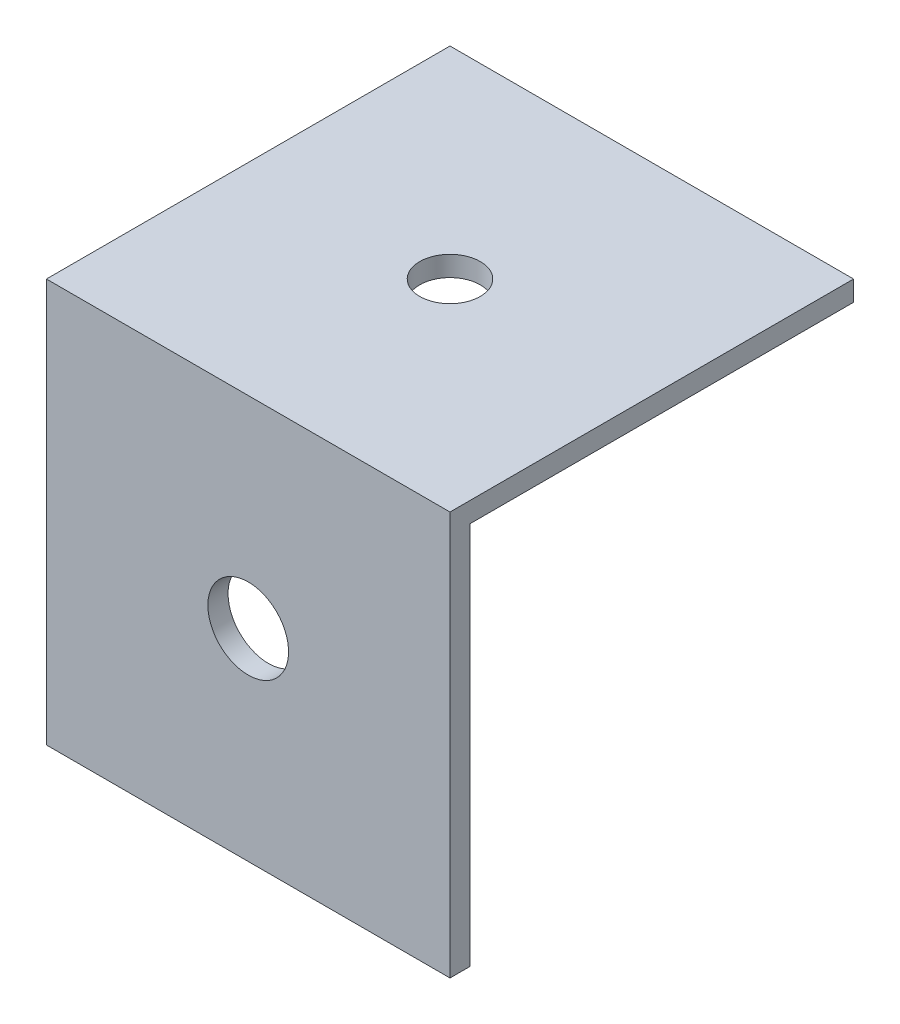
SolidWorks part; units mm, degrees
ref_plane "Front" through (0, 0, 0) normal (0, 0, 1) x (1, 0, 0)
ref_plane "Top" through (0, 0, 0) normal (0, 1, 0) x (1, 0, 0)
ref_plane "Right" through (0, 0, 0) normal (1, 0, 0) x (0, 0, -1)
sketch "草图1" plane through (0, 0, 0) normal (1, 0, 0) x (0, 0, -1)
  line L0 (0, 0) -> (0, 20)
  line L1 (0, 20) -> (20, 20)
  line L2 (20, 20) -> (20, 19)
  line L3 (20, 19) -> (1, 19)
  line L4 (1, 19) -> (1, 0)
  line L5 (1, 0) -> (0, 0)
  dimension "D1" = 20
  dimension "D2" = 20
  dimension "D3" = 1
  dimension "D4" = 19
extrude "凸台-拉伸1" add sketch "草图1" along normal blind 20
sketch "草图2" plane through (0, 0, -1) normal (0, 0, -1) x (-1, 0, 0)
  line L0 (-10, 19) -> (-10, 0) construction
  line L1 (-20, 19) -> (0, 19) construction
  line L2 (-20, 0) -> (0, 0) construction
  line L3 (-20, 20) -> (0, 20) construction
  circle A0 centre (-10, 10) radius 2
  dimension "D1" = 4
  dimension "D2" = 10
extrude "切除-拉伸1" cut sketch "草图2" against normal through all
sketch "草图3" plane through (0, 19, 0) normal (0, -1, 0) x (1, 0, 0)
  line L0 (0, -10) -> (20, -10) construction
  line L1 (0, -1) -> (0, -20) construction
  line L2 (20, -1) -> (20, -20) construction
  line L3 (20, 0) -> (0, 0) construction
  circle A0 centre (10, -10) radius 1.5
  circle A1 centre (16, -10) radius 1.5 construction
  dimension "D2" = 3
  dimension "D3" = 3
  dimension "D1" = 10
  dimension "D4" = 10
  dimension "D5" = 4
extrude "切除-拉伸2" cut sketch "草图3" against normal through all
